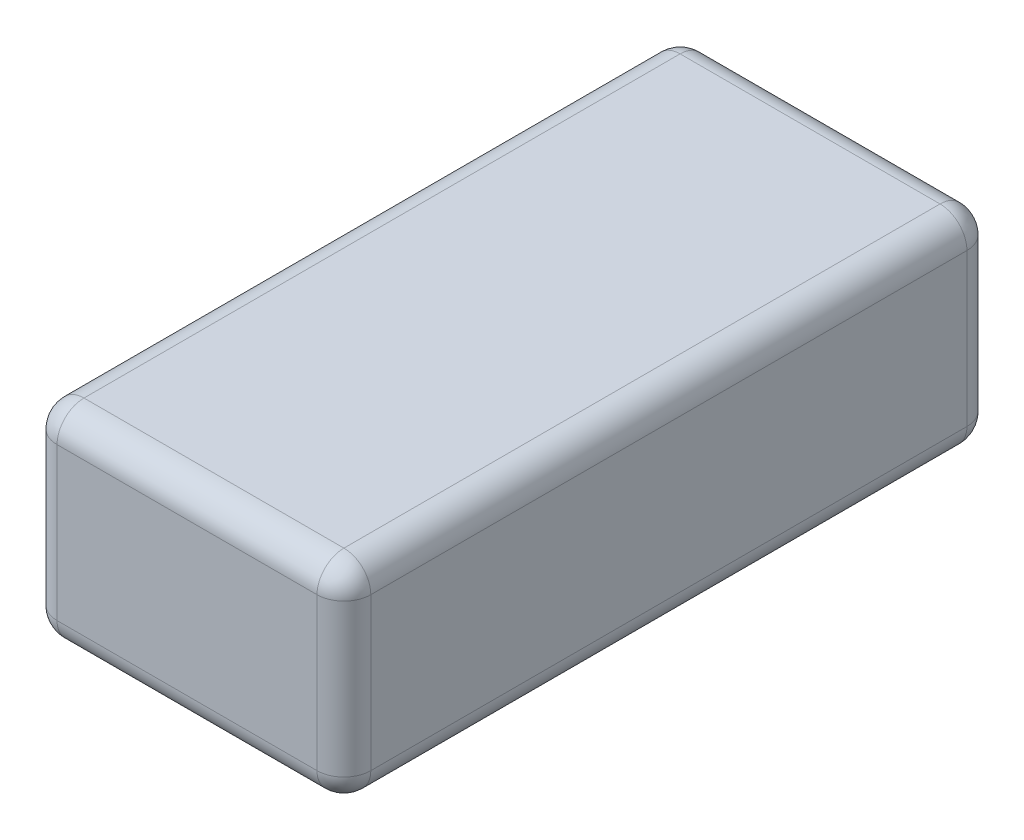
SolidWorks part; units mm, degrees
ref_plane "Front Plane" through (0, 0, 0) normal (0, 0, 1) x (1, 0, 0)
ref_plane "Top Plane" through (0, 0, 0) normal (0, 1, 0) x (1, 0, 0)
ref_plane "Right Plane" through (0, 0, 0) normal (1, 0, 0) x (0, 0, -1)
sketch "Sketch1" plane through (0, 0, 0) normal (0, 1, 0) x (1, 0, 0)
  line L1 (-17.5, 36.25) -> (17.5, 36.25)
  line L2 (-17.5, 36.25) -> (-17.5, -36.25)
  line L3 (-17.5, -36.25) -> (17.5, -36.25)
  line L4 (17.5, 36.25) -> (17.5, -36.25)
  line L5 (-17.5, 36.25) -> (17.5, -36.25) construction
  line L6 (-17.5, -36.25) -> (17.5, 36.25) construction
  point P0 (0, 0)
  dimension "D1" = 72.5
  dimension "D2" = 35
extrude "Boss-Extrude1" add sketch "Sketch1" along normal blind 23
fillet "Fillet1" radius 3 12 edges at (-17.5, 11.5, -36.25) (-17.5, 11.5, 36.25) (17.5, 11.5, 36.25) (17.5, 11.5, -36.25) (0, 0, -36.25) (-17.5, 0, 0) (0, 0, 36.25) (17.5, 0, 0) (0, 23, 36.25) (-17.5, 23, 0) (0, 23, -36.25) (17.5, 23, 0)
